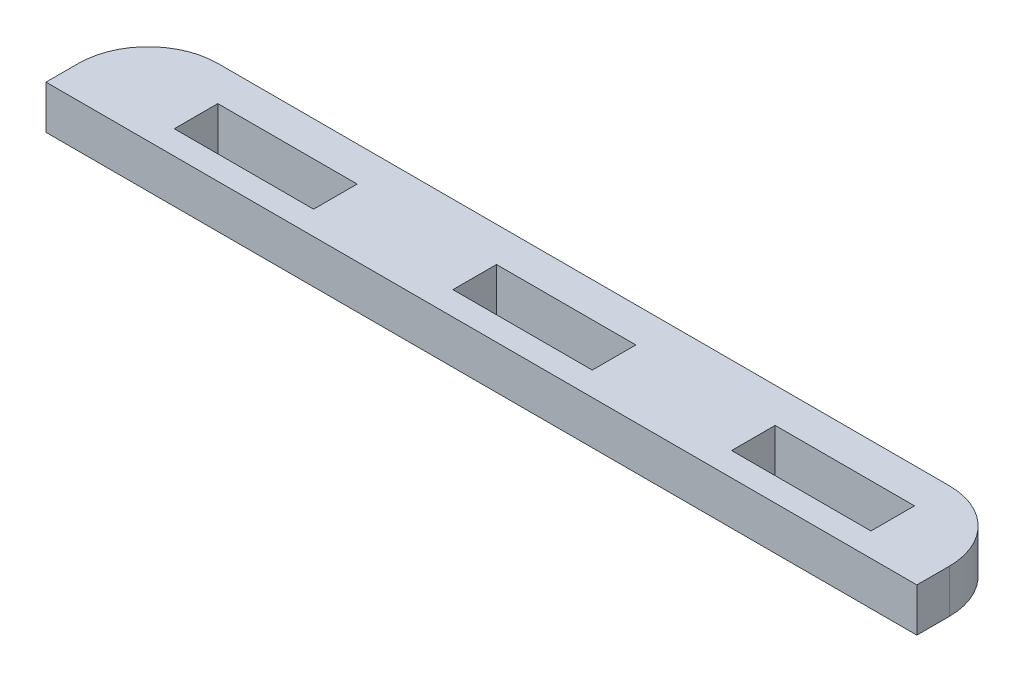
SolidWorks part; units mm, degrees
ref_plane "Front Plane" through (0, 0, 0) normal (0, 0, 1) x (1, 0, 0)
ref_plane "Top Plane" through (0, 0, 0) normal (0, 1, 0) x (1, 0, 0)
ref_plane "Right Plane" through (0, 0, 0) normal (1, 0, 0) x (0, 0, -1)
sketch "Sketch1" plane through (0, 0, 0) normal (0, 1, 0) x (1, 0, 0)
  line L0 (26.67, -10.033) -> (31.75, -10.033) construction
  line L1 (31.75, 18.288) -> (-31.75, 18.288)
  line L2 (31.75, 18.288) -> (31.75, -15.113)
  line L3 (31.75, -15.113) -> (-31.75, -15.113)
  line L4 (-31.75, 18.288) -> (-31.75, -15.113)
  line L5 (26.67, -10.033) -> (26.67, -15.113) construction
  line L6 (-26.67, -10.033) -> (-31.75, -10.033) construction
  line L7 (-26.67, 10.033) -> (26.67, 10.033) construction
  line L8 (-26.67, 10.033) -> (-26.67, -10.033) construction
  line L9 (-26.67, -10.033) -> (26.67, -10.033) construction
  line L10 (26.67, 10.033) -> (26.67, -10.033) construction
  line L11 (-26.67, 10.033) -> (26.67, -10.033) construction
  line L12 (-26.67, -10.033) -> (26.67, 10.033) construction
  line L13 (26.67, 15.748) -> (26.67, 18.288) construction
  line L14 (26.67, 15.748) -> (16.51, 15.748)
  line L15 (26.67, 15.748) -> (26.67, 12.573)
  line L16 (26.67, 12.573) -> (16.51, 12.573)
  line L17 (16.51, 15.748) -> (16.51, 12.573)
  line L18 (26.67, 15.748) -> (16.51, 12.573) construction
  line L19 (26.67, 12.573) -> (16.51, 15.748) construction
  line L20 (26.67, 12.573) -> (26.67, 10.033) construction
  line L21 (6.35, 15.748) -> (6.35, 12.573)
  line L22 (6.35, 15.748) -> (-3.81, 15.748)
  line L23 (6.35, 12.573) -> (-3.81, 12.573)
  line L24 (-3.81, 15.748) -> (-3.81, 12.573)
  line L25 (-13.97, 15.748) -> (-13.97, 12.573)
  line L26 (-13.97, 15.748) -> (-24.13, 15.748)
  line L27 (-13.97, 12.573) -> (-24.13, 12.573)
  line L28 (-24.13, 15.748) -> (-24.13, 12.573)
  line L30 (-20.32, -10.033) -> (20.32, -10.033)
  line L31 (-20.32, -10.033) -> (-20.32, 10.033)
  line L32 (-20.32, 10.033) -> (20.32, 10.033)
  line L33 (20.32, -10.033) -> (20.32, 10.033)
  line L34 (-20.32, -10.033) -> (20.32, 10.033) construction
  line L35 (-20.32, 10.033) -> (20.32, -10.033) construction
  point P0 (0, 0)
  point P4 (21.59, 14.1605)
  point P6 (0, 0)
  point P20 (0, 0)
  dimension "D1" = 20.066
  dimension "D2" = 53.34
  dimension "D3" = 5.08
  dimension "D4" = 3.175
  dimension "D5" = 10.16
  dimension "D6" = 2.54
  dimension "D7" = 3
  dimension "D8" = 6.35
extrude "Main Extrusion" add sketch "Sketch1" along normal blind 3.175
sketch "Sketch3" plane through (0, 3.175, 0) normal (0, 1, 0) x (1, 0, 0)
  line L0 (-26.7208, 6.3627) -> (-26.7208, 3.5687) construction
  line L1 (26.7208, -9.9949) -> (-26.7208, -9.9949) construction
  line L2 (26.7208, -9.9949) -> (26.7208, 9.9949) construction
  line L3 (26.7208, 9.9949) -> (-26.7208, 9.9949) construction
  line L5 (26.7208, -9.9949) -> (-26.7208, 9.9949) construction
  line L6 (26.7208, 9.9949) -> (-26.7208, -9.9949) construction
  line L7 (-26.7208, -3.5687) -> (-26.7208, -6.3627) construction
  line L8 (-26.7208, -6.3627) -> (-26.7208, -9.9949) construction
  line L9 (-26.7208, 6.3627) -> (-26.7208, 9.9949) construction
  line L10 (-24.9922, 4.9657) -> (-24.9922, -4.9657) construction
  line L14 (0, 9.9949) -> (0, -9.9949) construction
  circle A0 centre (-24.9922, 4.9657) radius 2.2225
  circle A1 centre (-24.9922, -4.9657) radius 2.2225
  circle A2 centre (24.9922, -4.9657) radius 2.2225
  circle A3 centre (24.9922, 4.9657) radius 2.2225
  point P0 (0, 0)
  dimension "D3" = 4.445
  dimension "D1" = 53.4416
  dimension "D2" = 19.9898
  dimension "D4" = 2.794
  dimension "D5" = 9.9314
extrude "Mounting Holes" cut sketch "Sketch3" against normal through all
sketch "Sketch5" plane through (0, 3.175, 0) normal (0, 1, 0) x (1, 0, 0)
  line L0 (-20.32, 0) -> (-20.32, 0.889)
  line L1 (-20.32, 10.033) -> (-20.32, -10.033) construction
  line L2 (-20.32, 0.889) -> (-27.305, 0.889)
  line L3 (-27.305, 0.889) -> (-27.305, -0.889)
  line L4 (-27.305, -0.889) -> (-20.32, -0.889)
  line L5 (-20.32, -0.889) -> (-20.32, 0)
  line L6 (0, 10.033) -> (0, -10.033) construction
  line L7 (20.32, 10.033) -> (-20.32, 10.033) construction
  line L8 (-20.32, -10.033) -> (20.32, -10.033) construction
  line L9 (27.305, -0.889) -> (20.32, -0.889)
  line L10 (27.305, 0.889) -> (27.305, -0.889)
  line L11 (20.32, 0.889) -> (27.305, 0.889)
  line L12 (20.32, -0.889) -> (20.32, 0)
  line L13 (20.32, 0) -> (20.32, 0.889)
  dimension "D1" = 6.985
  dimension "D2" = 1.778
extrude "Tab cutout" cut sketch "Sketch5" against normal through all
fillet "Fillet1" radius 5.08 4 edges at (31.75, 1.5875, -18.288) (31.75, 1.5875, 15.113) (-31.75, 1.5875, 15.113) (-31.75, 1.5875, -18.288)
sketch "Sketch6" plane through (0, 3.175, 0) normal (0, 1, 0) x (1, 0, 0)
  line L1 (-34.8908, 10.8416) -> (34.6314, 10.8416)
  line L2 (-34.8908, 10.8416) -> (-34.8908, -18.4792)
  line L3 (-34.8908, -18.4792) -> (34.6314, -18.4792)
  line L4 (34.6314, 10.8416) -> (34.6314, -18.4792)
extrude "Cut-Extrude3" cut sketch "Sketch6" against normal through all
sketch "Sketch7" plane through (0, 3.175, 0) normal (0, 1, 0) x (1, 0, 0)
  line L13 (26.5938, 12.6492) -> (26.5938, 15.6718)
  line L14 (-14.0462, 12.6492) -> (-14.0462, 15.6718)
  line L15 (-24.0538, 12.6492) -> (-14.0462, 12.6492)
  line L16 (-24.0538, 15.6718) -> (-24.0538, 12.6492)
  line L17 (-14.0462, 15.6718) -> (-24.0538, 15.6718)
  line L18 (-14.0462, 12.6492) -> (-14.0462, 15.6718)
  line L19 (-24.0538, 12.6492) -> (-14.0462, 12.6492)
  line L20 (-24.0538, 15.6718) -> (-24.0538, 12.6492)
  line L21 (-14.0462, 15.6718) -> (-24.0538, 15.6718)
  line L22 (16.5862, 12.6492) -> (26.5938, 12.6492)
  line L23 (16.5862, 15.6718) -> (16.5862, 12.6492)
  line L24 (26.5938, 15.6718) -> (16.5862, 15.6718)
  line L25 (26.5938, 12.6492) -> (26.5938, 15.6718)
  line L26 (16.5862, 12.6492) -> (26.5938, 12.6492)
  line L27 (16.5862, 15.6718) -> (16.5862, 12.6492)
  line L31 (26.5938, 15.6718) -> (16.5862, 15.6718)
  line L32 (6.2738, 12.6492) -> (6.2738, 15.6718)
  line L33 (6.2738, 15.6718) -> (-3.7338, 15.6718)
  line L34 (-3.7338, 12.6492) -> (6.2738, 12.6492)
  line L35 (-3.7338, 15.6718) -> (-3.7338, 12.6492)
  line L36 (6.2738, 12.6492) -> (6.2738, 15.6718)
  line L37 (6.2738, 15.6718) -> (-3.7338, 15.6718)
  line L38 (-3.7338, 12.6492) -> (6.2738, 12.6492)
  line L39 (-3.7338, 15.6718) -> (-3.7338, 12.6492)
  line L54 (-31.8262, 13.208) -> (-31.8262, 10.7654)
  line L55 (-31.8262, 10.7654) -> (31.8262, 10.7654)
  line L56 (31.8262, 10.7654) -> (31.8262, 13.208)
  line L57 (26.67, 18.3642) -> (-26.67, 18.3642)
  line L58 (-31.8262, 13.208) -> (-31.8262, 10.7654)
  line L59 (-31.8262, 10.7654) -> (31.8262, 10.7654)
  line L60 (31.8262, 10.7654) -> (31.8262, 13.208)
  line L61 (26.67, 18.3642) -> (-26.67, 18.3642)
  arc A9 (-26.67, 18.3642) -> (-31.8262, 13.208) centre (-26.67, 13.208) ccw
  arc A10 (31.8262, 13.208) -> (26.67, 18.3642) centre (26.67, 13.208) ccw
  arc A11 (-26.67, 18.3642) -> (-31.8262, 13.208) centre (-26.67, 13.208) ccw
  arc A12 (31.8262, 13.208) -> (26.67, 18.3642) centre (26.67, 13.208) ccw
  dimension "D1" = 0.0762
  dimension "D2" = 0.0762
  dimension "D3" = 0.0762
  dimension "D4" = 0.0762
